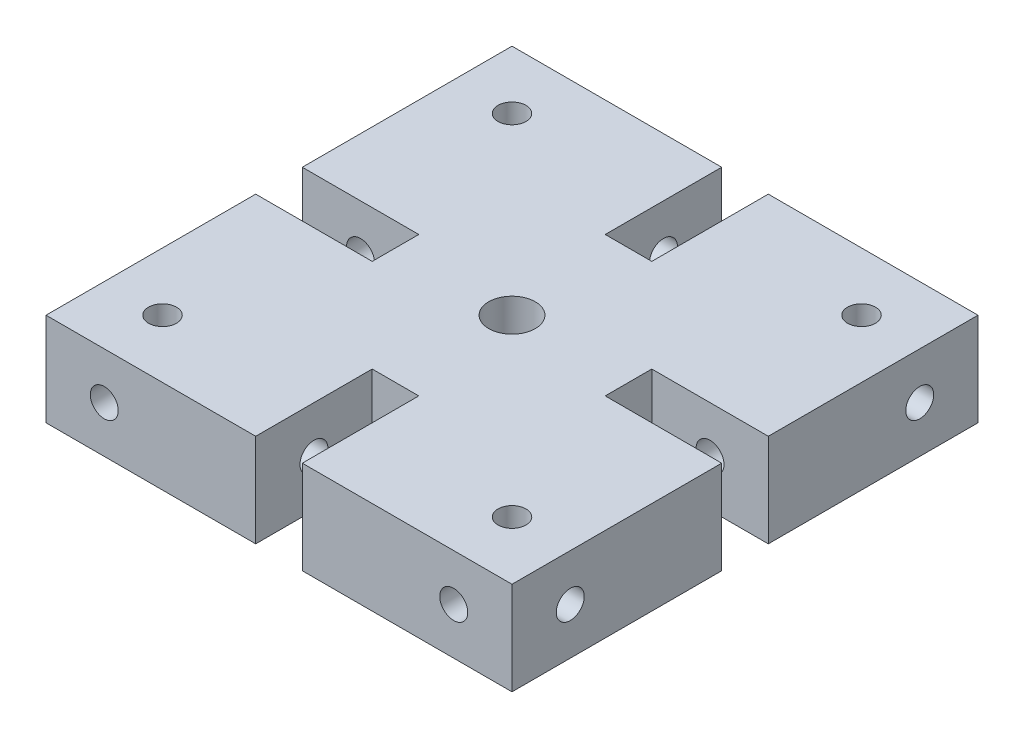
SolidWorks part; units mm, degrees
ref_plane "Front Plane" through (0, 0, 0) normal (0, 0, 1) x (1, 0, 0)
ref_plane "Top Plane" through (0, 0, 0) normal (0, 1, 0) x (1, 0, 0)
ref_plane "Right Plane" through (0, 0, 0) normal (1, 0, 0) x (0, 0, -1)
sketch "Sketch1" plane through (0, 0, 0) normal (0, 1, 0) x (1, 0, 0)
  line L0 (-7.5, 12.5) -> (-7.5, 25)
  line L1 (12.5, -12.5) -> (-12.5, -12.5)
  line L2 (12.5, -12.5) -> (12.5, 12.5)
  line L3 (12.5, 12.5) -> (-12.5, 12.5)
  line L4 (-12.5, -12.5) -> (-12.5, 12.5)
  line L5 (12.5, -12.5) -> (-12.5, 12.5) construction
  line L6 (12.5, 12.5) -> (-12.5, -12.5) construction
  line L7 (-7.5, 25) -> (-2.5, 25)
  line L8 (-2.5, 25) -> (-2.5, 12.5)
  line L9 (0, -1000) -> (0, 49000) construction
  line L10 (-1000, 0) -> (49000, 0) construction
  line L11 (2.5, 25) -> (2.5, 12.5)
  line L12 (7.5, 25) -> (2.5, 25)
  line L13 (7.5, 12.5) -> (7.5, 25)
  line L14 (7.5, -12.5) -> (7.5, -25)
  line L15 (7.5, -25) -> (2.5, -25)
  line L16 (2.5, -25) -> (2.5, -12.5)
  line L17 (-2.5, -25) -> (-2.5, -12.5)
  line L18 (-7.5, -25) -> (-2.5, -25)
  line L19 (-7.5, -12.5) -> (-7.5, -25)
  line L20 (12.5, 7.5) -> (25, 7.5)
  line L21 (25, 7.5) -> (25, 2.5)
  line L22 (25, 2.5) -> (12.5, 2.5)
  line L23 (12.5, -7.5) -> (25, -7.5)
  line L24 (25, -2.5) -> (12.5, -2.5)
  line L25 (25, -7.5) -> (25, -2.5)
  line L26 (-12.5, -7.5) -> (-25, -7.5)
  line L27 (-25, -7.5) -> (-25, -2.5)
  line L28 (-25, -2.5) -> (-12.5, -2.5)
  line L29 (-25, 2.5) -> (-12.5, 2.5)
  line L30 (-25, 7.5) -> (-25, 2.5)
  line L31 (-12.5, 7.5) -> (-25, 7.5)
  line L33 (25, -25) -> (-25, -25)
  line L34 (25, -25) -> (25, 25)
  line L35 (25, 25) -> (-25, 25)
  line L36 (-25, -25) -> (-25, 25)
  line L37 (25, -25) -> (-25, 25) construction
  line L38 (25, 25) -> (-25, -25) construction
  point P0 (0, 0)
  point P42 (0, 0)
  dimension "D1" = 25
  dimension "D2" = 12.5
  dimension "D3" = 5
  dimension "D4" = 5
  dimension "D5" = 12.5
  dimension "D6" = 5
  dimension "D7" = 5
  dimension "D8" = 50
extrude "Boss-Extrude1" add sketch "Sketch1" along normal blind 10 contours L36 L31 L4 L3 L0 L35 | L8 L7 L0 L3 | L3 L13 L12 L11 | L34 L35 L13 L3 L2 L20 | L22 L21 L20 L2 | L23 L25 L24 L2 | L33 L34 L23 L2 L1 L14 | L16 L15 L14 L1 | L1 L19 L18 L17 | L36 L33 L19 L1 L4 L26 | L28 L27 L26 L4 | L4 L31 L30 L29 | L4 L1 L2 L3 L31
sketch "Sketch3" plane through (-2.5, 0, 0) normal (-1, 0, 0) x (0, 0, 1)
  line L3 (-25, 10) -> (-25, 0) construction
  line L4 (-2.5, 10) -> (-25, 10) construction
  circle A0 centre (-18.75, 5) radius 1.5
  dimension "D1" = 3
  dimension "D2" = 6.25
  dimension "D3" = 5
extrude "Cut-Extrude1" cut sketch "Sketch3" against normal through all both and the other way through all
mirror "Mirror1" about plane through (0, 0, 0) normal (0, 0, 1) of "Cut-Extrude1"
sketch "Sketch4" plane through (0, 0, 2.5) normal (0, 0, 1) x (1, 0, 0)
  line L2 (-25, 10) -> (-2.5, 10) construction
  line L3 (-25, 10) -> (-25, 0) construction
  circle A0 centre (-18.75, 5) radius 1.5
  dimension "D1" = 3
  dimension "D2" = 5
  dimension "D3" = 6.25
extrude "Cut-Extrude2" cut sketch "Sketch4" against normal through all both and the other way through all
mirror "Mirror2" about plane through (0, 0, 0) normal (1, 0, 0) of "Cut-Extrude2"
sketch "Sketch5" plane through (0, 10, 0) normal (0, 1, 0) x (1, 0, 0)
  circle A0 centre (0, 0) radius 2.5
  dimension "D1" = 5
extrude "Cut-Extrude3" cut sketch "Sketch5" against normal blind 10
sketch "Sketch9" plane through (0, 10, 0) normal (0, 1, 0) x (1, 0, 0)
  line L1 (18.75, -18.75) -> (-18.75, -18.75) construction
  line L2 (18.75, -18.75) -> (18.75, 18.75) construction
  line L3 (18.75, 18.75) -> (-18.75, 18.75) construction
  line L4 (-18.75, -18.75) -> (-18.75, 18.75) construction
  line L5 (18.75, -18.75) -> (-18.75, 18.75) construction
  line L6 (18.75, 18.75) -> (-18.75, -18.75) construction
  line L7 (-25, 25) -> (-2.5, 25) construction
  line L8 (-25, 2.5) -> (-25, 25) construction
  circle A0 centre (-18.75, 18.75) radius 1.5
  circle A1 centre (18.75, 18.75) radius 1.5
  circle A2 centre (18.75, -18.75) radius 1.5
  circle A3 centre (-18.75, -18.75) radius 1.5
  point P0 (0, 0)
  dimension "D3" = 3
  dimension "D1" = 6.25
  dimension "D2" = 6.25
extrude "Cut-Extrude4" cut sketch "Sketch9" against normal through all
